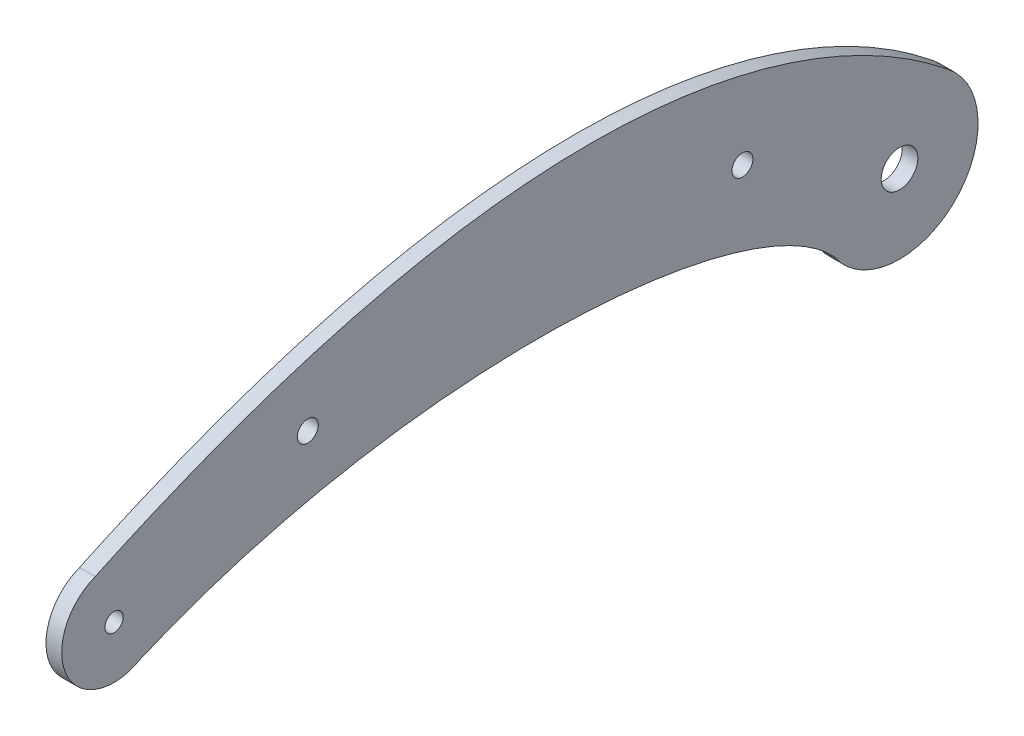
SolidWorks part; units mm, degrees
ref_plane "Alzado" through (0, 0, 0) normal (0, 0, 1) x (1, 0, 0)
ref_plane "Planta" through (0, 0, 0) normal (0, 1, 0) x (1, 0, 0)
ref_plane "Vista lateral" through (0, 0, 0) normal (1, 0, 0) x (0, 0, -1)
sketch "Croquis1" plane through (0, 0, 0) normal (1, 0, 0) x (0, 0, -1)
  line L0 (0, 0) -> (-150, 0) construction
  arc A0 (-12.4798, -8.322) -> (9.282, 11.7833) centre (0, 0) ccw
  arc A1 (-153.5894, 9.3336) -> (-144.8946, -8.5985) centre (-150, 0) ccw
  circle A2 centre (-150, 0) radius 1.75
  circle A3 centre (0, 0) radius 3.5
  circle A4 centre (-113, 13.1172) radius 2
  circle A5 centre (-30, 15.6148) radius 2
  spline S0 degree 3 poles (-144.8946, -8.5985) (-94.3996, 13.0893) (-29.0218, 9.6082) (-12.4798, -8.322) knots 0 0 0 0 1 1 1 1
  spline S1 degree 3 poles (-153.5894, 9.3336) (-52.0275, 57.0175) (-3.0287, 21.6661) (9.282, 11.7833) knots 0 0 0 0 1 1 1 1
  dimension "D1" = 3.5
  dimension "D2" = 4
  dimension "D3" = 9.282
  dimension "D4" = 12.4798
  dimension "D5" = 30
  dimension "D6" = 113
  dimension "D7" = 144.8946
  dimension "D8" = 153.5894
  dimension "D9" = 13.1172
  dimension "D10" = 15.6148
extrude "Saliente-Extruir1" add sketch "Croquis1" along normal blind 3
